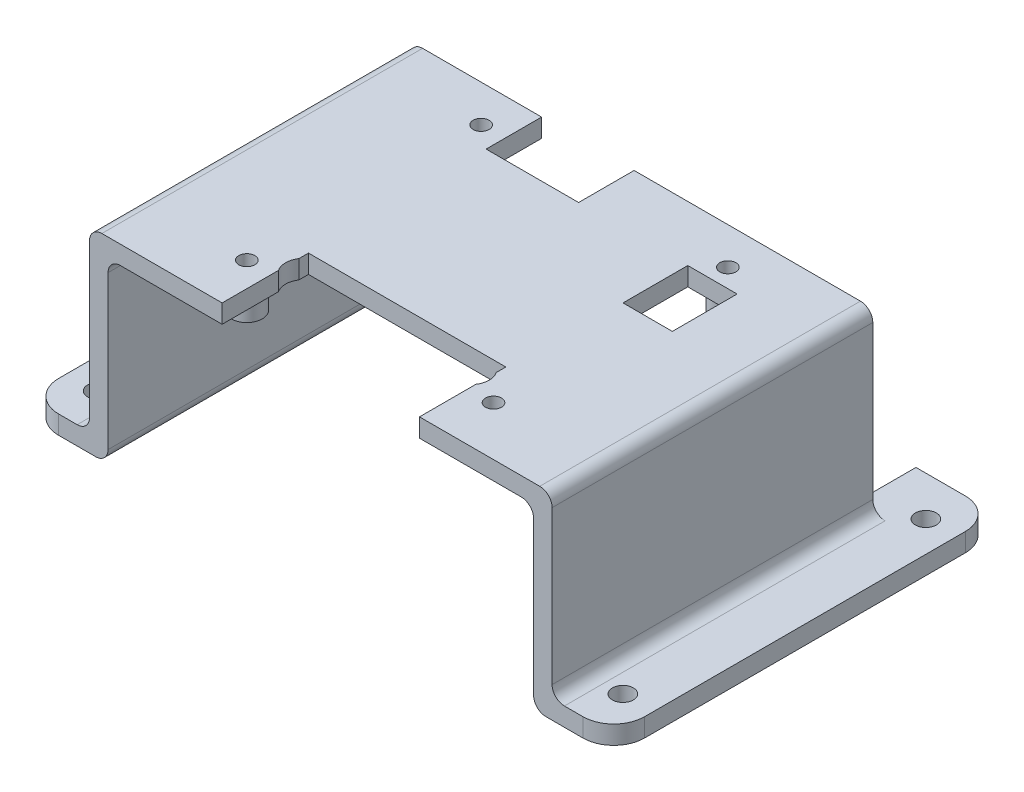
SolidWorks part; units mm, degrees
ref_plane "Front Plane" through (0, 0, 0) normal (0, 0, 1) x (1, 0, 0)
ref_plane "Top Plane" through (0, 0, 0) normal (0, 1, 0) x (1, 0, 0)
ref_plane "Right Plane" through (0, 0, 0) normal (1, 0, 0) x (0, 0, -1)
sketch "Sketch1" plane through (0, 0, 0) normal (0, 1, 0) x (1, 0, 0)
  line L0 (90.0435, 55.565) -> (90.0435, 6.435) construction
  line L1 (0, 0) -> (95, 0)
  line L2 (0, 0) -> (0, 62)
  line L3 (0, 62) -> (95, 62)
  line L4 (95, 0) -> (95, 62)
  line L5 (4.9565, 55.565) -> (4.9565, 6.435) construction
  line L6 (4.9565, 55.565) -> (90.0435, 55.565) construction
  circle A0 centre (90.0435, 55.565) radius 1.7
  circle A1 centre (90.0435, 6.435) radius 1.7
  circle A2 centre (4.9565, 55.565) radius 1.7
  circle A3 centre (4.9565, 6.435) radius 1.7
  point P9 (0, 31)
  point P10 (90.0435, 31)
  point P15 (4.9565, 31)
  point P16 (95, 31)
  point P17 (47.5, 55.565)
  point P18 (47.5, 62)
  dimension "D3" = 3.4
  dimension "D4" = 3.4
  dimension "D5" = 49.13
  dimension "D6" = 3.4
  dimension "D7" = 3.4
  dimension "D1" = 62
  dimension "D2" = 95
  dimension "D8" = 49.13
  dimension "D9" = 85.087
extrude "Boss-Extrude1" add sketch "Sketch1" along normal blind 3
sketch "Sketch2" plane through (0, 3, 0) normal (0, 1, 0) x (1, 0, 0)
  line L0 (4.9565, 55.565) -> (90.0435, 55.565) construction
  line L1 (10, 52) -> (85, 52)
  line L2 (10, 52) -> (10, 0)
  line L3 (10, 0) -> (85, 0)
  line L4 (85, 52) -> (85, 0)
  line L5 (4.9565, 6.435) -> (90.0435, 6.435) construction
  line L6 (95, 62) -> (0, 62) construction
  line L7 (0, 0) -> (95, 0) construction
  point P15 (47.5, 62)
  point P16 (47.5, 52)
  dimension "D1" = 75
  dimension "D2" = 10
  dimension "D3" = 0
extrude "Boss-Extrude2" add sketch "Sketch2" along normal blind 28.85
sketch "Sketch3" plane through (0, 0, 0) normal (0, 0, 1) x (1, 0, 0)
  line L0 (10, 31.85) -> (85, 31.85) construction
  line L1 (13, 28.85) -> (82, 28.85)
  line L2 (13, 28.85) -> (13, 3)
  line L3 (13, 3) -> (82, 3)
  line L4 (82, 28.85) -> (82, 3)
  line L5 (10, 31.85) -> (10, 3) construction
  line L6 (85, 31.85) -> (85, 3) construction
  line L7 (10, 3) -> (0, 3) construction
  dimension "D1" = 3
  dimension "D2" = 3
  dimension "D3" = 3
extrude "Cut-Extrude1" cut sketch "Sketch3" against normal through all
sketch "Sketch4" plane through (0, 0, 0) normal (0, 0, 1) x (1, 0, 0)
  line L0 (0, 0) -> (95, 0) construction
  line L1 (13, 3) -> (82, 3)
  line L2 (13, 3) -> (13, 0)
  line L3 (13, 0) -> (82, 0)
  line L4 (82, 3) -> (82, 0)
extrude "Cut-Extrude2" cut sketch "Sketch4" against normal through all
sketch "Sketch5" plane through (0, 31.85, 0) normal (0, 1, 0) x (1, 0, 0)
  line L0 (85, 52) -> (10, 52) construction
  line L1 (27.5, 46) -> (67.5, 46) construction
  line L2 (27.5, 46) -> (27.5, 8) construction
  line L3 (27.5, 8) -> (67.5, 8) construction
  line L4 (67.5, 46) -> (67.5, 8) construction
  line L6 (47.5, 46) -> (47.5, 8) construction
  line L7 (10, 0) -> (85, 0) construction
  line L8 (63.5, 0) -> (31.5, 0)
  line L9 (63.5, 0) -> (63.5, 14)
  line L10 (63.5, 14) -> (31.5, 14)
  line L11 (31.5, 0) -> (31.5, 14)
  circle A0 centre (27.5, 46) radius 1.3
  circle A1 centre (27.5, 8) radius 1.3
  circle A2 centre (67.5, 8) radius 1.3
  circle A3 centre (67.5, 46) radius 1.3
  point P6 (47.5, 52)
  point P7 (47.5, 46)
  point P24 (47.5, 14)
  dimension "D3" = 2.6
  dimension "D4" = 2.6
  dimension "D1" = 40
  dimension "D2" = 38
  dimension "D5" = 14
  dimension "D6" = 32
  dimension "5" = 8
extrude "Cut-Extrude3" cut sketch "Sketch5" against normal through all
sketch "Sketch7" plane through (0, 31.85, 0) normal (0, 1, 0) x (1, 0, 0)
  line L2 (47.5, 14) -> (47.5, 3.8387) construction
  line L3 (63.5, 14) -> (31.5, 14) construction
  circle A0 centre (34, 10.8) radius 3
  circle A5 centre (61, 10.8) radius 3
  circle A6 centre (27.5, 8) radius 1.3 construction
  dimension "D1" = 6
  dimension "D2" = 2.8
extrude "Cut-Extrude5" cut sketch "Sketch7" against normal through all
sketch "Sketch6" plane through (0, 31.85, 0) normal (0, 1, 0) x (1, 0, 0)
  line L0 (85, 52) -> (10, 52) construction
  line L1 (31.3, 52) -> (46.3, 52)
  line L2 (31.3, 52) -> (31.3, 43)
  line L3 (31.3, 43) -> (46.3, 43)
  line L4 (46.3, 52) -> (46.3, 43)
  line L5 (85, 0) -> (85, 52) construction
  line L6 (64, 43) -> (72, 43)
  line L7 (64, 43) -> (64, 32.5)
  line L8 (64, 32.5) -> (72, 32.5)
  line L9 (72, 43) -> (72, 32.5)
  circle A0 centre (67.5, 46) radius 1.3 construction
  circle A1 centre (27.5, 46) radius 1.3 construction
  point P12 (67.5, 46)
  point P13 (68, 43)
  dimension "D1" = 3
  dimension "D2" = 8
  dimension "D3" = 9
  dimension "D4" = 15
  dimension "D5" = 3.8
  dimension "D6" = 10.5
  dimension "D7" = 17
extrude "Cut-Extrude4" cut sketch "Sketch6" against normal through all
fillet "Fillet1" radius 2 8 edges at (10, 3, -26) (85, 3, -26) (10, 31.85, -26) (85, 31.85, -26) (13, 28.85, -26) (82, 28.85, -26) (13, 0, -31) (82, 0, -31)
sketch "Sketch8" plane through (0, 28.85, 0) normal (0, -1, 0) x (1, 0, 0)
  circle A0 centre (27.5, -8) radius 1.3
  circle A1 centre (27.5, -8) radius 2.5
  circle A2 centre (67.5, -8) radius 1.3
  circle A3 centre (67.5, -8) radius 2.5
  circle A4 centre (67.5, -8) radius 1.3 construction
  circle A5 centre (27.5, -46) radius 1.3
  circle A6 centre (27.5, -46) radius 2.5
  circle A7 centre (27.5, -46) radius 1.3 construction
  circle A8 centre (67.5, -46) radius 1.3
  circle A9 centre (67.5, -46) radius 2.5
  circle A10 centre (67.5, -46) radius 1.3 construction
  dimension "D1" = 5
  dimension "D2" = 2.6
  dimension "D3" = 5
  dimension "D4" = 2.6
  dimension "D5" = 5
  dimension "D6" = 2.6
  dimension "D7" = 5
  dimension "D8" = 2.6
extrude "Boss-Extrude4" add sketch "Sketch8" along normal blind 4
fillet "Fillet2" radius 5 4 edges at (0, 1.5, -62) (95, 1.5, -62) (95, 1.5, 0) (0, 1.5, 0)
